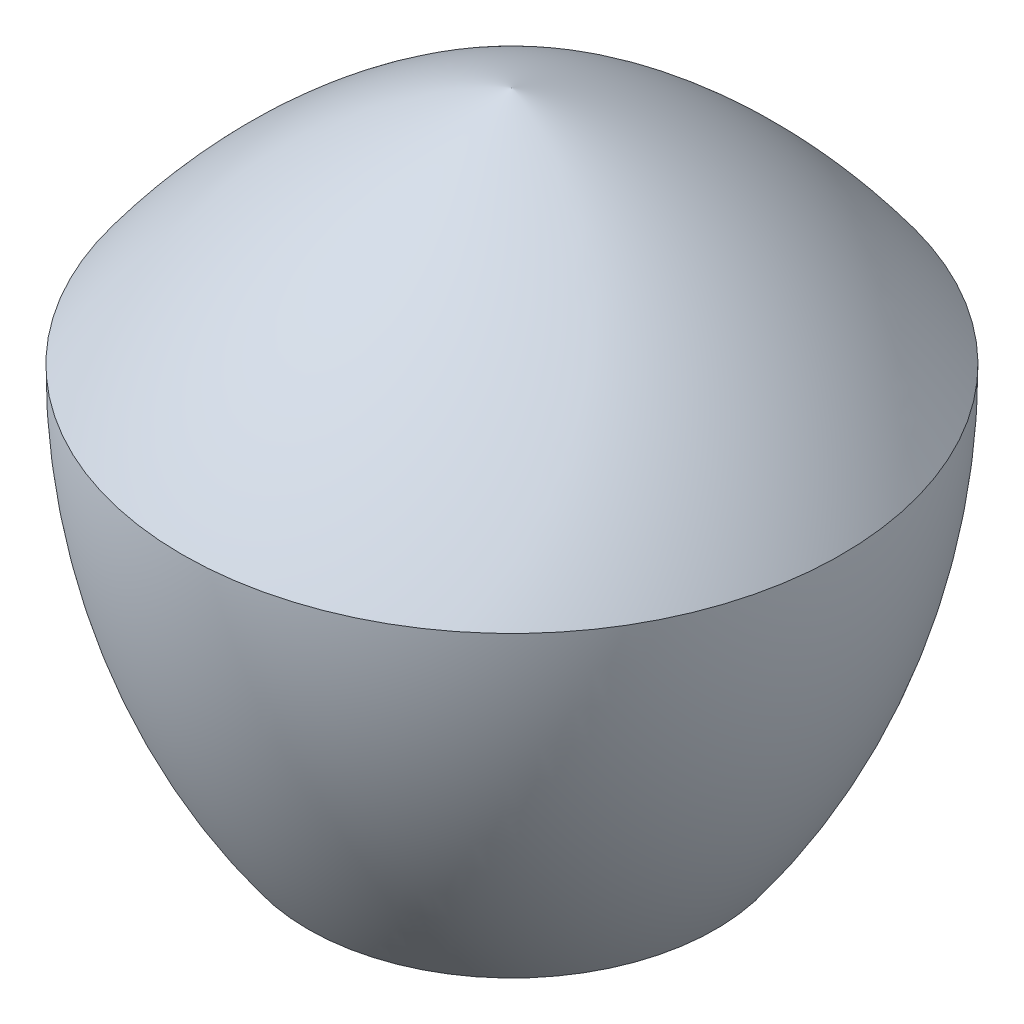
SolidWorks part; units mm, degrees
ref_plane "Front Plane" through (0, 0, 0) normal (0, 0, 1) x (1, 0, 0)
ref_plane "Top Plane" through (0, 0, 0) normal (0, 1, 0) x (1, 0, 0)
ref_plane "Right Plane" through (0, 0, 0) normal (1, 0, 0) x (0, 0, -1)
sketch "Sketch1" plane through (0, 0, 0) normal (0, 0, 1) x (1, 0, 0)
  line L0 (0, 55.7674) -> (0, -62.6888) construction
  line L1 (-0.1809, 26.1551) -> (-49.4573, -9.6462) construction
  line L2 (-24.9309, 7.9103) -> (-6.109, -50.0175) construction
  line L3 (-15.2272, -21.2663) -> (45.6817, -21.2663) construction
  line L4 (15.52, -21.0536) -> (34.3418, 36.8742) construction
  line L5 (51.1659, -10.8877) -> (1.8896, 24.9137) construction
  line L6 (0, 26.2866) -> (0, -23.7134)
  circle A0 centre (0, 0) radius 21.2663 construction
  arc A1 (0, 26.2866) -> (25, 8.123) centre (-15.4508, -21.2663) cw
  arc A2 (25, 8.123) -> (15.4508, -21.2663) centre (-25, 8.123) cw
  arc A3 (15.4508, -21.2663) -> (0, -23.7134) centre (0, 26.2866) cw
  dimension "D1" = 50
revolve "Revolve1" add sketch "Sketch1" angle 360 about L0
scale "Scale1" scale about centroid uniform scaling yes scale factor 0.5
